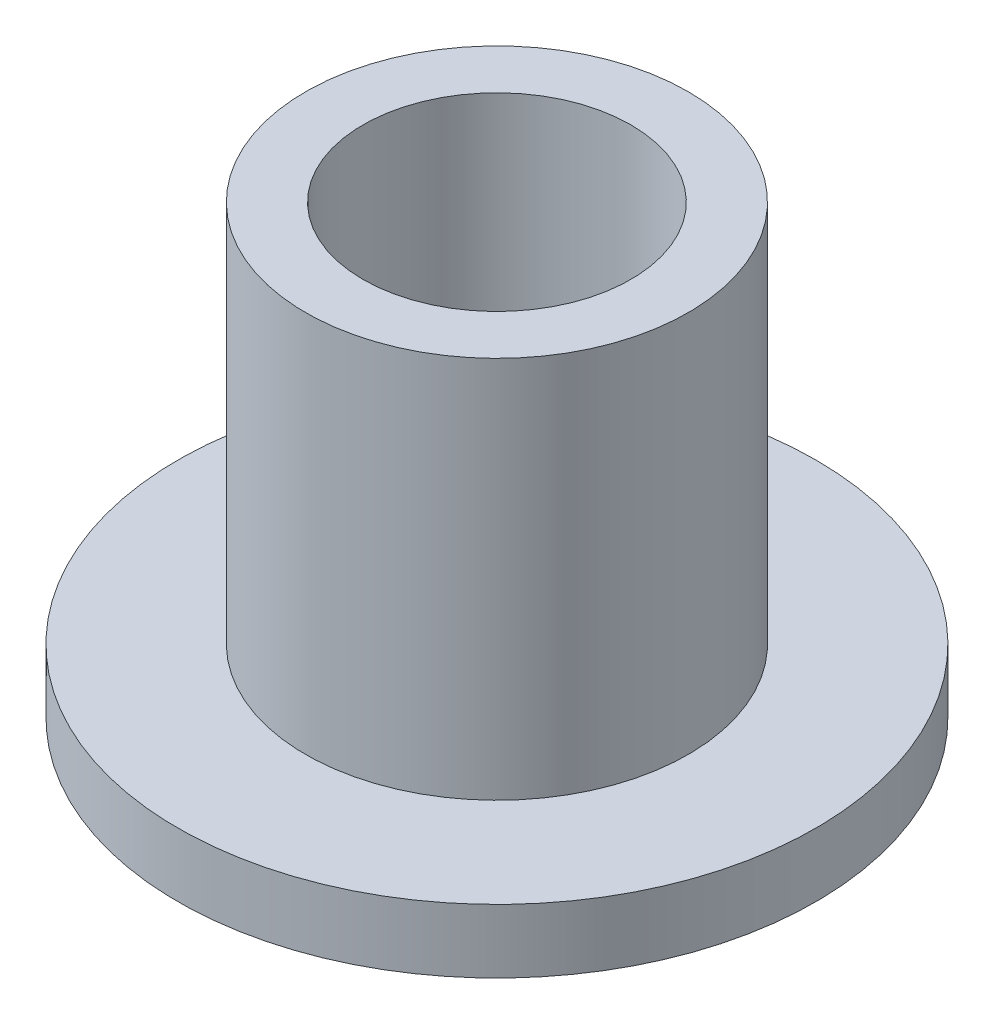
SolidWorks part; units mm, degrees
material "PTFE (general)"
ref_plane "Front" through (0, 0, 0) normal (0, 0, 1) x (1, 0, 0)
ref_plane "Top" through (0, 0, 0) normal (0, 1, 0) x (1, 0, 0)
ref_plane "Side" through (0, 0, 0) normal (1, 0, 0) x (0, 0, -1)
sketch "Sketch1" plane through (0, 0, 0) normal (0, 0, 1) x (1, 0, 0)
  line L0 (0, 0) -> (0, 5.9498) construction
  line L1 (0, 0) -> (-5, 0)
  line L2 (-5, 0) -> (-5, 1)
  line L3 (-5, 1) -> (-3, 1)
  line L4 (-3, 1) -> (-3, 7)
  line L5 (-3, 7) -> (0, 7)
  line L6 (0, 7) -> (0, 0)
  dimension "D1" = 10
  dimension "D2" = 6
  dimension "D3" = 1
  dimension "D4" = 6
revolve "Revolve1" add sketch "Sketch1" angle 360 about L0
hole_wizard "Ø4.2mm Dowel Hole1" positions "Sketch2" profile "Sketch3" hole size "Ø4.0" standard "ANSI Metric" end condition through all
sketch "Sketch2" plane through (0, 7, 0) normal (0, 1, 0) x (1, 0, 0)
  point P0 (0, 0)
sketch "Sketch3" plane through (0, 7, 0) normal (1, 0, 0) x (0, 0, 1)
  line L0 (0, 0) -> (0, 7)
  line L1 (0, 7) -> (2.1, 7)
  line L2 (2.1, 7) -> (2.1, 0)
  line L5 (2.1, 0) -> (0, 0)
  line L11 (0, -6.35) -> (0, 107.95) construction
  dimension "Thru Hole Dia." = 4.2
  dimension "Thru Hole Depth" = 7
